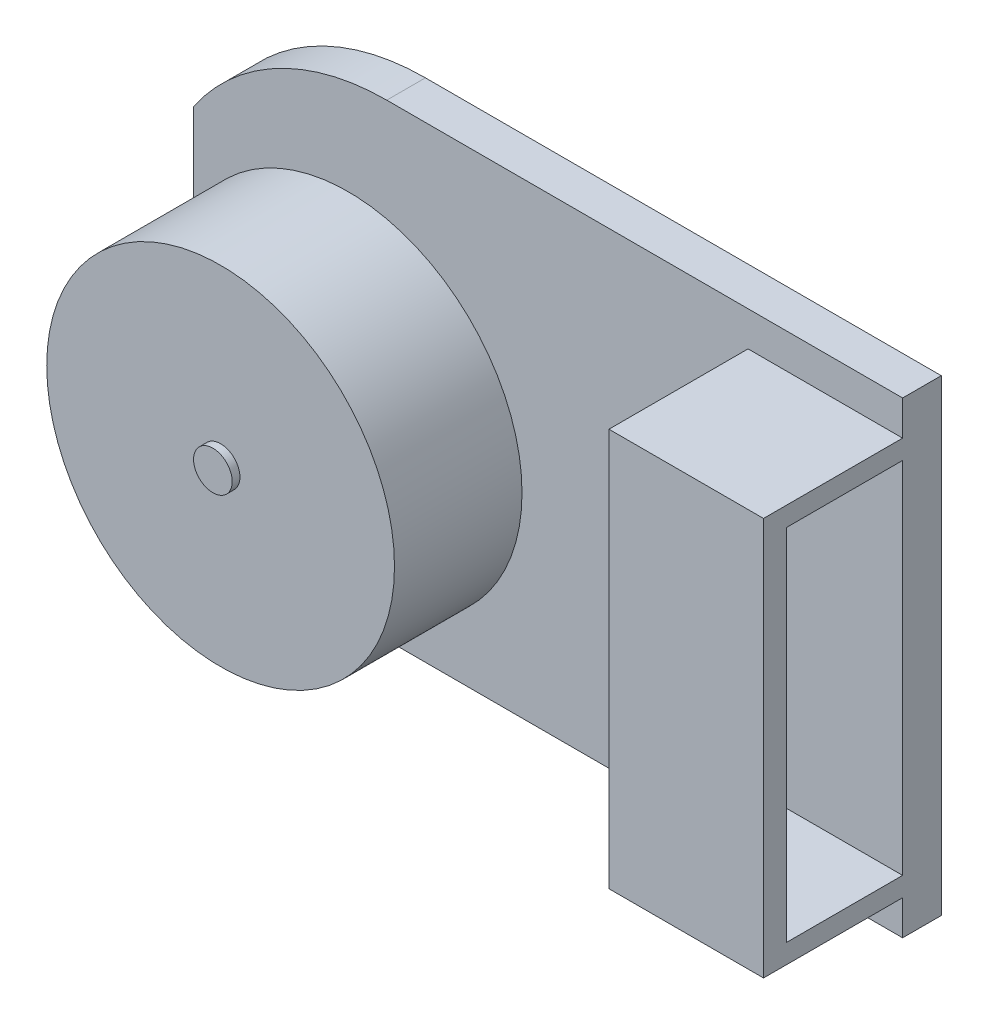
SolidWorks part; units mm, degrees
ref_plane "前视基准面" through (0, 0, 0) normal (0, 0, 1) x (1, 0, 0)
ref_plane "上视基准面" through (0, 0, 0) normal (0, 1, 0) x (1, 0, 0)
ref_plane "右视基准面" through (0, 0, 0) normal (1, 0, 0) x (0, 0, -1)
sketch "草图1" plane through (0, 0, 0) normal (0, 0, 1) x (1, 0, 0)
  line L0 (0, 6.05) -> (13.35, 6.05)
  line L2 (-5, -3.4062) -> (-5, 3.4062)
  line L4 (5, -3.4062) -> (5, 3.4062)
  line L5 (-3.8541, -4.6635) -> (3.8541, 4.6635) construction
  line L6 (-3.8541, 4.6635) -> (3.8541, -4.6635) construction
  line L7 (13.35, 6.05) -> (13.35, -6.05)
  line L8 (0, 0) -> (2.9783, 0) construction
  line L9 (0, -6.05) -> (13.35, -6.05)
  arc A0 (-5, -3.4062) -> (5, -3.4062) centre (0, 0) ccw
  arc A1 (5, 3.4062) -> (-5, 3.4062) centre (0, 0) ccw
  circle A2 centre (0, 0) radius 0.5
  point P18 (13.35, 0)
  dimension "D1" = 6.05
  dimension "D2" = 18.35
  dimension "D3" = 10
extrude "凸台-拉伸1" add sketch "草图1" along normal blind 1 contours L4 A1 L2 A0 A2 | A1 L4 A0 L9 L7 L0
sketch "草图3" plane through (0, 0, 0) normal (0, 0, -1) x (-1, 0, 0)
  circle A0 centre (0, 0) radius 0.5
extrude "凸台-拉伸2" add sketch "草图3" against normal blind 5.5
ref_plane "基准面4" through (0, 0, 2) normal (0, 0, 1) x (1, 0, 0)
ref_plane "基准面5" through (0, 0, 5.3) normal (0, 0, 1) x (1, 0, 0)
sketch "草图4" plane through (0, 0, 2) normal (0, 0, 1) x (1, 0, 0)
  circle A0 centre (0, 0) radius 4.5
extrude "凸台-拉伸3" add sketch "草图4" along normal up to surface (3.3 mm away) up to plane "基准面5"
sketch "草图5" plane through (0, 0, 1) normal (0, 0, 1) x (1, 0, 0)
  line L0 (13.35, 0) -> (13.35, 5.15)
  line L1 (13.35, 6.05) -> (13.35, -6.05) construction
  line L2 (13.35, 5.15) -> (9.35, 5.15)
  line L3 (9.35, 5.15) -> (9.35, -5.15)
  line L4 (13.35, 0) -> (14.9224, 0) construction
  line L5 (13.35, -5.15) -> (9.35, -5.15)
  line L6 (13.35, 0) -> (13.35, -5.15)
  point P9 (9.35, 0)
extrude "凸台-拉伸4" add sketch "草图5" along normal blind 3.6
sketch "草图6" plane through (0, 0, 1) normal (0, 0, 1) x (1, 0, 0)
  line L0 (9.85, 4.65) -> (12.85, 4.65)
  line L1 (9.35, 5.15) -> (13.35, 5.15)
  line L2 (9.35, 5.15) -> (9.35, -5.15)
  line L3 (9.35, -5.15) -> (13.35, -5.15)
  line L4 (13.35, 5.15) -> (13.35, -5.15)
  line L5 (12.85, 4.65) -> (12.85, -4.65)
  line L6 (9.85, -4.65) -> (12.85, -4.65)
  line L7 (9.85, 4.65) -> (9.85, -4.65)
  line L8 (12.85, 4.65) -> (13.35, 4.65)
  line L9 (13.35, 4.65) -> (13.35, -4.65)
  line L10 (13.35, -4.65) -> (12.85, -4.65)
  dimension "D1" = 0.5
extrude "切除-拉伸1" cut sketch "草图6" along normal blind 3 contours L0 L7 L6 L5 | L10 L4 L8 L5
